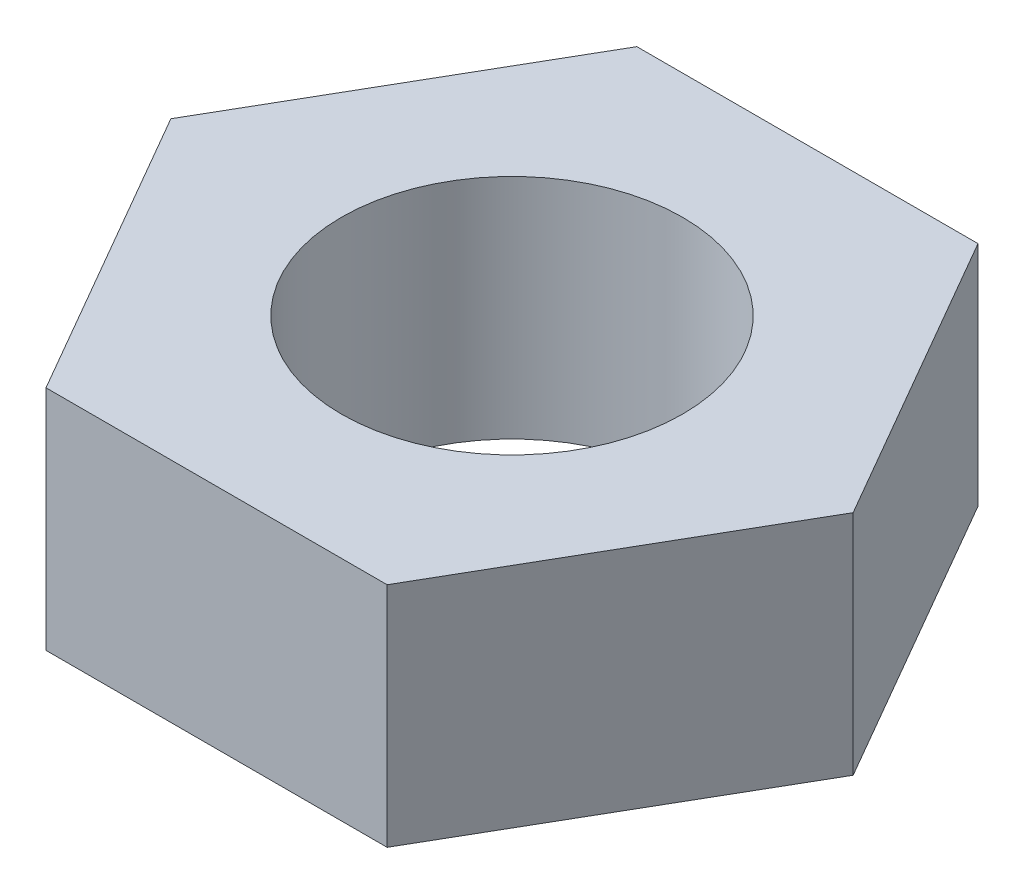
SolidWorks part; units mm, degrees
ref_plane "Front Plane" through (0, 0, 0) normal (0, 0, 1) x (1, 0, 0)
ref_plane "Top Plane" through (0, 0, 0) normal (0, 1, 0) x (1, 0, 0)
ref_plane "Right Plane" through (0, 0, 0) normal (1, 0, 0) x (0, 0, -1)
sketch "Sketch1" plane through (0, 0, 0) normal (0, 1, 0) x (1, 0, 0)
  line L0 (-3, 0) -> (-1.5, 2.5981)
  line L1 (-1.5, 2.5981) -> (1.5, 2.5981)
  line L2 (1.5, 2.5981) -> (3, 0)
  line L3 (3, 0) -> (1.5, -2.5981)
  line L4 (1.5, -2.5981) -> (-1.5, -2.5981)
  line L5 (-1.5, -2.5981) -> (-3, 0)
  line L6 (-1.5, 2.5981) -> (1.5, -2.5981) construction
  line L7 (-1.5, -2.5981) -> (1.5, 2.5981) construction
  line L8 (3, 0) -> (-3, 0) construction
  circle A0 centre (0, 0) radius 1.5
  circle A1 centre (0, 0) radius 3 construction
  point P6 (-1.4999, 2.5981)
  point P10 (0, 0)
  dimension "D1" = 3
  dimension "D4" = 6
  dimension "D2" = 120
  dimension "D3" = 120
extrude "Boss-Extrude1" add sketch "Sketch1" along normal blind 2
